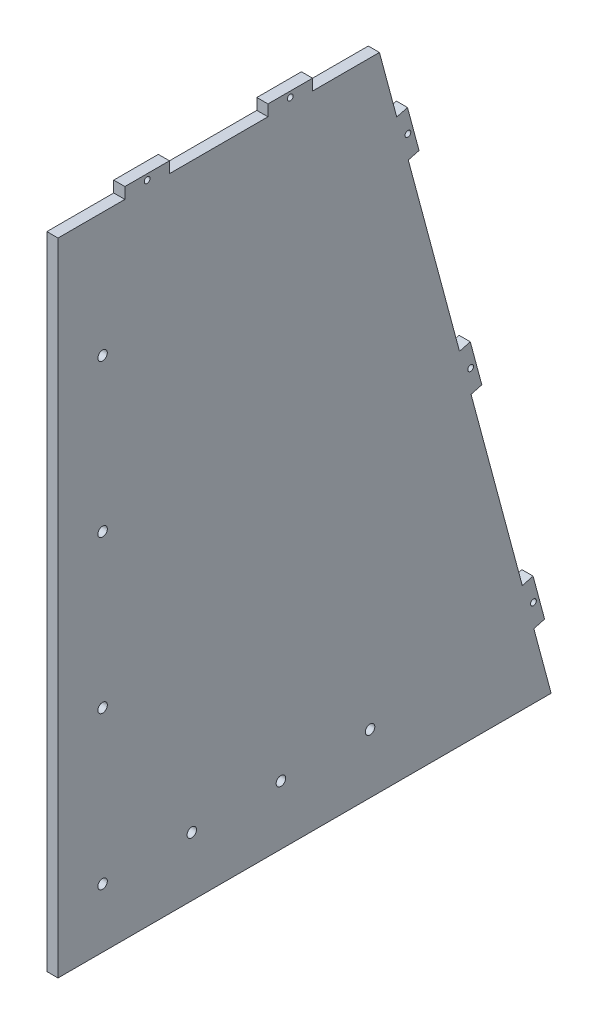
SolidWorks part; units mm, degrees
material "Pine"
ref_plane "Front Plane" through (0, 0, 0) normal (0, 0, 1) x (1, 0, 0)
ref_plane "Top Plane" through (0, 0, 0) normal (0, 1, 0) x (1, 0, 0)
ref_plane "Right Plane" through (0, 0, 0) normal (1, 0, 0) x (0, 0, -1)
ref_plane "Plane1" through (-388.62, 0, 0) normal (-1, 0, 0) x (0, -1, 0)
sketch "Sketch1" plane through (-388.62, 0, 0) normal (-1, 0, 0) x (0, -1, 0)
  line L0 (-371.45, -148.8119) -> (-365.1, -148.8119)
  line L1 (-365.1, -148.8119) -> (-365.1, -186.9119)
  line L2 (-365.1, -186.9119) -> (-328.2982, -196.7729)
  line L3 (-328.2982, -196.7729) -> (-329.9417, -202.9065)
  line L4 (-329.9417, -202.9065) -> (-305.4072, -209.4805)
  line L5 (-305.4072, -209.4805) -> (-303.7637, -203.3469)
  line L6 (-303.7637, -203.3469) -> (-194.8173, -232.539)
  line L7 (-194.8173, -232.539) -> (-196.4608, -238.6726)
  line L8 (-196.4608, -238.6726) -> (-171.9262, -245.2466)
  line L9 (-171.9262, -245.2466) -> (-170.2827, -239.113)
  line L10 (-170.2827, -239.113) -> (-61.3363, -268.3051)
  line L11 (-61.3363, -268.3051) -> (-62.9798, -274.4387)
  line L12 (-62.9798, -274.4387) -> (-38.4453, -281.0127)
  line L13 (-38.4453, -281.0127) -> (-36.8018, -274.8791)
  line L14 (-36.8018, -274.8791) -> (0, -284.7401)
  line L15 (0, -284.7401) -> (0, -3.7883)
  line L16 (0, -3.7883) -> (-365.1, -3.7883)
  line L17 (-365.1, -3.7883) -> (-365.1, -41.8883)
  line L18 (-365.1, -41.8883) -> (-371.45, -41.8883)
  line L19 (-371.45, -41.8883) -> (-371.45, -67.2883)
  line L20 (-371.45, -67.2883) -> (-365.1, -67.2883)
  line L21 (-365.1, -67.2883) -> (-365.1, -123.4119)
  line L22 (-365.1, -123.4119) -> (-371.45, -123.4119)
  line L23 (-371.45, -123.4119) -> (-371.45, -148.8119)
  circle A0 centre (-49.8908, -274.6589) radius 1.65
  circle A1 centre (-368.275, -54.5883) radius 1.65
  circle A2 centre (-183.3718, -238.8928) radius 1.65
  circle A3 centre (-368.275, -136.1119) radius 1.65
  circle A4 centre (-316.8527, -203.1267) radius 1.65
  circle A5 centre (-294.45, -29.1883) radius 2.7
  circle A6 centre (-207.55, -29.1883) radius 2.7
  circle A7 centre (-120.65, -29.1883) radius 2.7
  circle A8 centre (-33.749, -181.5883) radius 2.7
  circle A9 centre (-33.749, -29.1883) radius 2.7
  circle A10 centre (-33.749, -130.7883) radius 2.7
  circle A11 centre (-33.749, -79.9883) radius 2.7
extrude "Boss-Extrude1" add sketch "Sketch1" against normal blind 6.35
